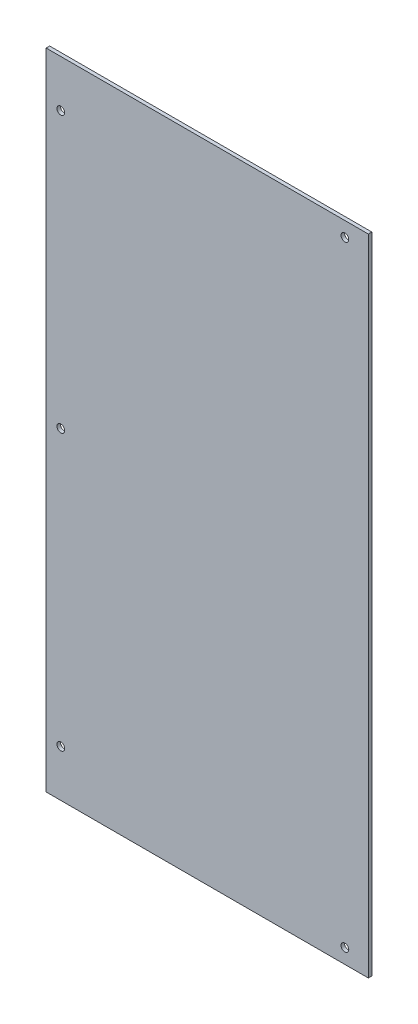
SolidWorks part; units mm, degrees
material "Acrylic (Medium-high impact)"
ref_plane "Front Plane" through (0, 0, 0) normal (0, 0, 1) x (1, 0, 0)
ref_plane "Top Plane" through (0, 0, 0) normal (0, 1, 0) x (1, 0, 0)
ref_plane "Right Plane" through (0, 0, 0) normal (1, 0, 0) x (0, 0, -1)
sketch "Sketch1" plane through (0, 0, 0) normal (0, 0, 1) x (1, 0, 0)
  line L1 (0, 0) -> (275, 0)
  line L2 (0, 0) -> (0, 550)
  line L3 (0, 550) -> (275, 550)
  line L4 (275, 0) -> (275, 550)
  dimension "D1" = 275
  dimension "D2" = 550
extrude "Boss-Extrude1" add sketch "Sketch1" along normal blind 3
hole_wizard "M6 Clearance Hole1" positions "Sketch2" profile "Sketch3" hole size "M6" standard "ANSI Metric" end condition through all
sketch "Sketch2" plane through (0, 0, 3) normal (0, 0, 1) x (1, 0, 0)
  line L1 (275, 550) -> (0, 550) construction
  line L2 (0, 550) -> (0, 0) construction
  line L3 (0, 0) -> (275, 0) construction
  line L4 (275, 0) -> (275, 550) construction
  line L5 (275, 550) -> (0, 550) construction
  point P0 (12.5, 275)
  point P2 (12.5, 510)
  point P4 (12.5, 40)
  point P10 (255, 12.5)
  point P14 (255, 537.5)
  point P40 (0, 275)
  dimension "D1" = 40
  dimension "D2" = 12.5
  dimension "D3" = 40
  dimension "D4" = 20
  dimension "D5" = 12.5
  dimension "D6" = 12.5
sketch "Sketch3" plane through (12.5, 275, 3) normal (1, 0, 0) x (0, -1, 0)
  line L0 (0, 0) -> (0, 3)
  line L1 (0, 3) -> (3.3, 3)
  line L2 (3.3, 3) -> (3.3, 0)
  line L5 (3.3, 0) -> (0, 0)
  line L11 (0, -6.35) -> (0, 107.95) construction
  dimension "Thru Hole Dia." = 6.6
  dimension "Thru Hole Depth" = 3
